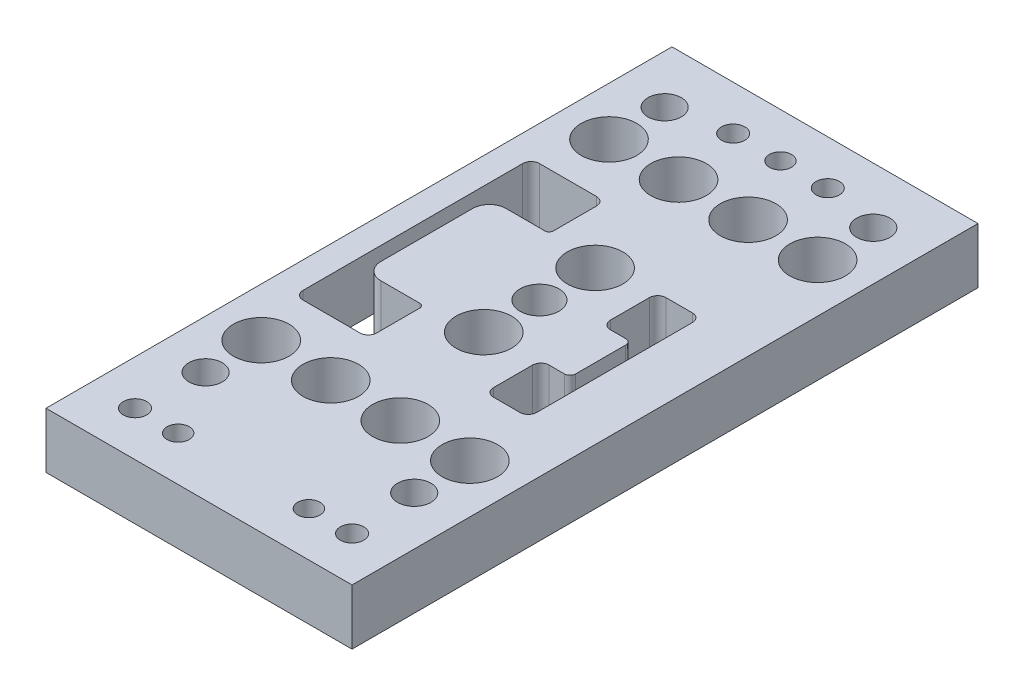
SolidWorks part; units mm, degrees
material "Plain Carbon Steel"
ref_plane "Front Plane" through (0, 0, 0) normal (0, 0, 1) x (1, 0, 0)
ref_plane "Top Plane" through (0, 0, 0) normal (0, 1, 0) x (1, 0, 0)
ref_plane "Right Plane" through (0, 0, 0) normal (1, 0, 0) x (0, 0, -1)
sketch "Sketch1" plane through (0, 0, 0) normal (0, 1, 0) x (1, 0, 0)
  line L1 (-55, -112.5) -> (55, -112.5)
  line L2 (-55, -112.5) -> (-55, 112.5)
  line L3 (-55, 112.5) -> (55, 112.5)
  line L4 (55, -112.5) -> (55, 112.5)
  line L5 (-55, -112.5) -> (55, 112.5) construction
  line L6 (-55, 112.5) -> (55, -112.5) construction
  point P0 (0, 0)
  dimension "D1" = 225
  dimension "D2" = 110
extrude "Boss-Extrude1" add sketch "Sketch1" along normal blind 20
sketch "Sketch2" plane through (0, 20, 0) normal (0, 1, 0) x (1, 0, 0)
  line L0 (-42.5, 37.36) -> (-19, 37.36) construction
  line L1 (-42.5, -17.64) -> (-19, -17.64) construction
  line L8 (-40.5, 26.36) -> (-40.5, -6.64) construction
  line L9 (-42.5, -32.64) -> (-22, -32.64)
  line L11 (-42.5, 52.36) -> (-22, 52.36)
  line L13 (-20.5, 32.36) -> (-34.5, 32.36) construction
  line L14 (-19, 37.36) -> (-19, 33.86) construction
  line L16 (-45.5, 34.36) -> (-45.5, -14.64) construction
  line L18 (-19, -17.64) -> (-19, -14.14) construction
  line L19 (-34.5, -12.64) -> (-20.5, -12.64) construction
  line L20 (-40.5, 26.36) -> (-40.5, -6.64)
  line L21 (-20.5, 32.36) -> (-34.5, 32.36)
  line L22 (-19, 49.36) -> (-19, 33.86)
  line L24 (-45.5, 49.36) -> (-45.5, -29.64)
  line L26 (-19, -29.64) -> (-19, -14.14)
  line L27 (-34.5, -12.64) -> (-20.5, -12.64)
  arc A0 (-22, 52.36) -> (-19, 49.36) centre (-22, 49.36) cw
  arc A1 (-45.5, 49.36) -> (-42.5, 52.36) centre (-42.5, 49.36) cw
  arc A2 (-42.5, -32.64) -> (-45.5, -29.64) centre (-42.5, -29.64) cw
  arc A3 (-22, -32.64) -> (-19, -29.64) centre (-22, -29.64) ccw
  arc A6 (-40.5, -6.64) -> (-34.5, -12.64) centre (-34.5, -6.64) ccw construction
  arc A7 (-34.5, 32.36) -> (-40.5, 26.36) centre (-34.5, 26.36) ccw construction
  arc A8 (-20.5, 32.36) -> (-19, 33.86) centre (-20.5, 33.86) ccw construction
  arc A11 (-19, -14.14) -> (-20.5, -12.64) centre (-20.5, -14.14) ccw construction
  arc A12 (-40.5, -6.64) -> (-34.5, -12.64) centre (-34.5, -6.64) ccw
  arc A13 (-34.5, 32.36) -> (-40.5, 26.36) centre (-34.5, 26.36) ccw
  arc A14 (-20.5, 32.36) -> (-19, 33.86) centre (-20.5, 33.86) ccw
  arc A17 (-19, -14.14) -> (-20.5, -12.64) centre (-20.5, -14.14) ccw
  dimension "D3" = 3
  dimension "D1" = 15
  dimension "D2" = 15
extrude "Cut-Extrude1" cut sketch "Sketch2" against normal up to next
sketch "Sketch3" plane through (0, 20, 0) normal (0, 1, 0) x (1, 0, 0)
  line L0 (22, -8.64) -> (27.5, -8.64) construction
  line L1 (19, -13.64) -> (19, -11.64) construction
  line L3 (34.5, 15.36) -> (34.5, -10.64) construction
  line L5 (19, 18.36) -> (19, 16.36) construction
  line L6 (27.5, 13.36) -> (22, 13.36) construction
  line L7 (29.5, -6.64) -> (29.5, 11.36) construction
  line L8 (22, -8.64) -> (27.5, -8.64)
  line L9 (19, -25.64) -> (19, -11.64)
  line L11 (34.5, 30.36) -> (34.5, -25.64)
  line L13 (19, 30.36) -> (19, 16.36)
  line L14 (27.5, 13.36) -> (22, 13.36)
  line L15 (29.5, -6.64) -> (29.5, 11.36)
  line L16 (22, -28.64) -> (31.5, -28.64)
  line L17 (22, 33.36) -> (31.5, 33.36)
  line L18 (19, 18.36) -> (31.5, 18.36) construction
  line L19 (31.5, -13.64) -> (19, -13.64) construction
  arc A0 (27.5, -8.64) -> (29.5, -6.64) centre (27.5, -6.64) ccw construction
  arc A1 (22, -8.64) -> (19, -11.64) centre (22, -11.64) ccw construction
  arc A4 (19, 16.36) -> (22, 13.36) centre (22, 16.36) ccw construction
  arc A5 (29.5, 11.36) -> (27.5, 13.36) centre (27.5, 11.36) ccw construction
  arc A6 (27.5, -8.64) -> (29.5, -6.64) centre (27.5, -6.64) ccw
  arc A7 (22, -8.64) -> (19, -11.64) centre (22, -11.64) ccw
  arc A10 (19, 16.36) -> (22, 13.36) centre (22, 16.36) ccw
  arc A11 (29.5, 11.36) -> (27.5, 13.36) centre (27.5, 11.36) ccw
  arc A12 (22, 33.36) -> (19, 30.36) centre (22, 30.36) ccw
  arc A13 (31.5, 33.36) -> (34.5, 30.36) centre (31.5, 30.36) cw
  arc A14 (31.5, -28.64) -> (34.5, -25.64) centre (31.5, -25.64) ccw
  arc A15 (22, -28.64) -> (19, -25.64) centre (22, -25.64) cw
  dimension "D3" = 3
  dimension "D1" = 15
  dimension "D2" = 15
extrude "Cut-Extrude2" cut sketch "Sketch3" against normal up to next
sketch "Sketch4" plane through (0, 0, 0) normal (0, -1, 0) x (1, 0, 0)
  circle A0 centre (37.5, 52.64) radius 10 construction
  circle A1 centre (12.5, 52.64) radius 10 construction
  circle A2 centre (-12.5, 52.64) radius 10 construction
  circle A3 centre (-37.5, 52.64) radius 10 construction
  circle A4 centre (0, 10.14) radius 10 construction
  circle A5 centre (0, -29.86) radius 10 construction
  circle A6 centre (37.5, -72.36) radius 10 construction
  circle A7 centre (12.5, -72.36) radius 10 construction
  circle A8 centre (-12.5, -72.36) radius 10 construction
  circle A9 centre (-37.5, -72.36) radius 10 construction
  circle A10 centre (37.5, 52.64) radius 10
  circle A11 centre (12.5, 52.64) radius 10
  circle A12 centre (-12.5, 52.64) radius 10
  circle A13 centre (-37.5, 52.64) radius 10
  circle A14 centre (0, 10.14) radius 10
  circle A15 centre (0, -29.86) radius 10
  circle A16 centre (37.5, -72.36) radius 10
  circle A17 centre (12.5, -72.36) radius 10
  circle A18 centre (-12.5, -72.36) radius 10
  circle A19 centre (-37.5, -72.36) radius 10
extrude "Cut-Extrude3" cut sketch "Sketch4" against normal through all
sketch "Sketch5" plane through (0, 20, 0) normal (0, 1, 0) x (1, 0, 0)
  circle A0 centre (-37.5, 92.36) radius 6
  circle A1 centre (37.5, 92.36) radius 6
  circle A2 centre (-37.5, -72.64) radius 6
  circle A3 centre (37.5, -72.64) radius 6
  dimension "D1" = 12
extrude "Cut-Extrude4" cut sketch "Sketch5" against normal up to next
sketch "Sketch6" plane through (0, 20, 0) normal (0, 1, 0) x (1, 0, 0)
  circle A0 centre (0, 9.86) radius 7
  dimension "D1" = 14
extrude "Cut-Extrude5" cut sketch "Sketch6" against normal up to next
hole_wizard "CBORE for M8 Hex Socket Head Cap Screw1" positions "Sketch10" profile "Sketch9" counterbore size "M8" standard "ISO" end condition through all
sketch "Sketch10" plane through (0, 0, 0) normal (0, -1, 0) x (-1, 0, 0)
  line L0 (-55, -112.5) -> (-55, 112.5) construction
  line L1 (55, 112.5) -> (55, -112.5) construction
  line L2 (-55, 112.5) -> (55, 112.5) construction
  line L3 (55, -112.5) -> (-55, -112.5) construction
  point P0 (-17, 96.5)
  point P2 (17, 96.5)
  point P4 (-39, -96.5)
  point P6 (39, -96.5)
  dimension "D1" = 38
  dimension "D2" = 38
  dimension "D3" = 16
  dimension "D4" = 16
  dimension "D5" = 16
  dimension "D6" = 16
sketch "Sketch9" plane through (17, 0, -96.5) normal (1, 0, 0) x (0, 0, -1)
  line L0 (0, 0) -> (0, 20)
  line L1 (0, 20) -> (4.2, 20)
  line L3 (4.2, 20) -> (4.2, 8.6)
  line L4 (4.2, 8.6) -> (7.5, 8.6)
  line L5 (7.5, 8.6) -> (7.5, 0)
  line L7 (7.5, 0) -> (0, 0)
  line L11 (0, -6.35) -> (0, 107.95) construction
  dimension "Thru Hole Dia." = 8.4
  dimension "Thru Hole Depth" = 20
  dimension "C'Bore Dia." = 15
  dimension "C'Bore Depth" = 8.6
hole_wizard "Ø8.0mm Dowel Hole1" positions "Sketch13" profile "Sketch12" hole size "Ø8.0" standard "ISO" end condition through all
sketch "Sketch13" plane through (0, 0, 0) normal (0, -1, 0) x (-1, 0, 0)
  line L0 (-55, 112.5) -> (55, 112.5) construction
  line L1 (55, -112.5) -> (-55, -112.5) construction
  circle A2 centre (-39, -96.5) radius 7.5 construction
  circle A3 centre (39, -96.5) radius 7.5 construction
  point P0 (0, 96.5)
  point P2 (-23.5, -96.5)
  point P4 (23.5, -96.5)
  dimension "D3" = 8
  dimension "D4" = 8
  dimension "D1" = 16
  dimension "D2" = 16
sketch "Sketch12" plane through (0, 0, -96.5) normal (1, 0, 0) x (0, 0, -1)
  line L0 (0, 0) -> (0, 20)
  line L1 (0, 20) -> (4, 20)
  line L2 (4, 20) -> (4, 0)
  line L5 (4, 0) -> (0, 0)
  line L11 (0, -6.35) -> (0, 107.95) construction
  dimension "Thru Hole Dia." = 8
  dimension "Thru Hole Depth" = 20
